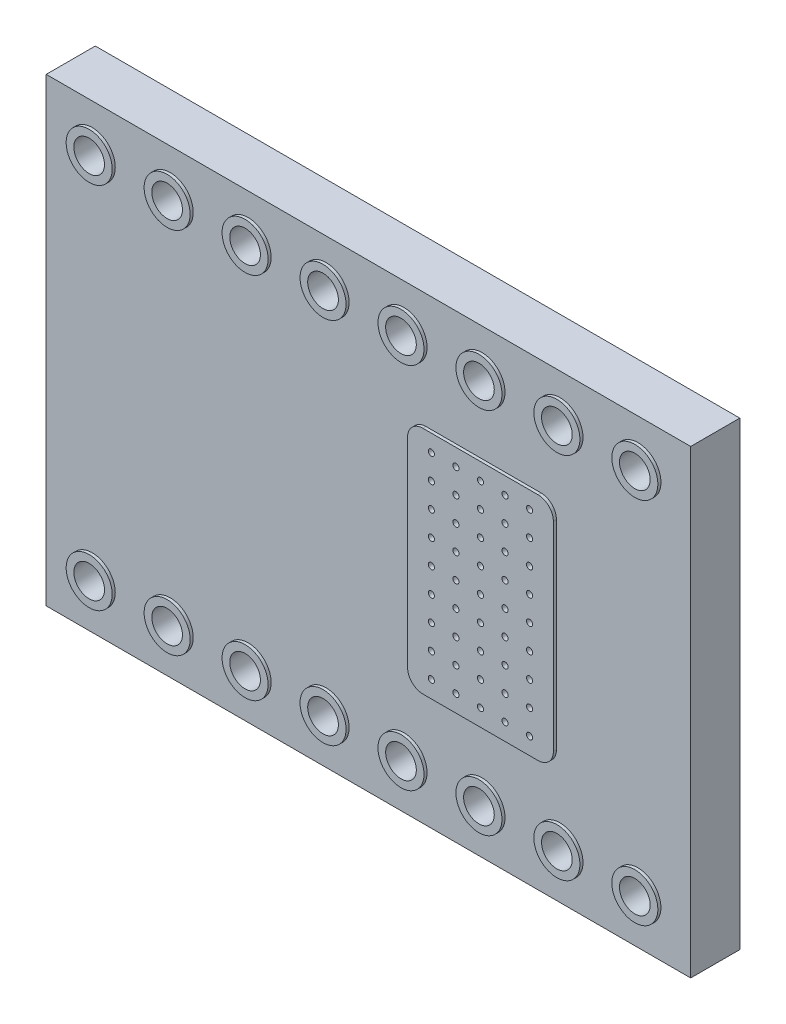
SolidWorks part; units mm, degrees
ref_plane "Front Plane" through (0, 0, 0) normal (0, 0, 1) x (1, 0, 0)
ref_plane "Top Plane" through (0, 0, 0) normal (0, 1, 0) x (1, 0, 0)
ref_plane "Right Plane" through (0, 0, 0) normal (1, 0, 0) x (0, 0, -1)
sketch "Sketch1" plane through (0, 0, 0) normal (0, 0, 1) x (1, 0, 0)
  line L1 (-10.5, 7.5) -> (10.5, 7.5)
  line L2 (-10.5, 7.5) -> (-10.5, -7.5)
  line L3 (-10.5, -7.5) -> (10.5, -7.5)
  line L4 (10.5, 7.5) -> (10.5, -7.5)
  line L5 (-10.5, 7.5) -> (10.5, -7.5) construction
  line L6 (-10.5, -7.5) -> (10.5, 7.5) construction
  point P0 (0, 0)
  dimension "D1" = 21
  dimension "D2" = 15
extrude "Boss-Extrude1" add sketch "Sketch1" along normal blind 1.6
sketch "Sketch2" plane through (0, 0, 1.6) normal (0, 0, 1) x (1, 0, 0)
  circle A0 centre (-9, 6) radius 0.75
  circle A1 centre (-9, -6) radius 0.75
  circle A2 centre (-6.46, 6) radius 0.75
  circle A3 centre (-6.46, -6) radius 0.75
  circle A4 centre (-3.92, 6) radius 0.75
  circle A5 centre (-3.92, -6) radius 0.75
  circle A6 centre (-1.38, 6) radius 0.75
  circle A7 centre (-1.38, -6) radius 0.75
  circle A8 centre (1.16, 6) radius 0.75
  circle A9 centre (1.16, -6) radius 0.75
  circle A10 centre (3.7, 6) radius 0.75
  circle A11 centre (3.7, -6) radius 0.75
  circle A12 centre (6.24, 6) radius 0.75
  circle A13 centre (6.24, -6) radius 0.75
  circle A14 centre (8.78, 6) radius 0.75
  circle A15 centre (8.78, -6) radius 0.75
  dimension "D3" = 1.5
  dimension "D4" = 1.5
  dimension "D1" = 12
  dimension "D2" = 6
  dimension "D6" = 9
  dimension "D5" = 8
extrude "Boss-Extrude2" add sketch "Sketch2" along normal blind 0.1 and the other way blind 1.7
sketch "Sketch3" plane through (0, 0, 1.7) normal (0, 0, 1) x (1, 0, 0)
  circle A0 centre (-9, 6) radius 0.5
  circle A1 centre (-9, -6) radius 0.5
  circle A2 centre (-6.46, 6) radius 0.5
  circle A3 centre (-6.46, -6) radius 0.5
  circle A4 centre (-3.92, 6) radius 0.5
  circle A5 centre (-3.92, -6) radius 0.5
  circle A6 centre (-1.38, 6) radius 0.5
  circle A7 centre (-1.38, -6) radius 0.5
  circle A8 centre (1.16, 6) radius 0.5
  circle A9 centre (1.16, -6) radius 0.5
  circle A10 centre (3.7, 6) radius 0.5
  circle A11 centre (3.7, -6) radius 0.5
  circle A12 centre (6.24, 6) radius 0.5
  circle A13 centre (6.24, -6) radius 0.5
  circle A14 centre (8.78, 6) radius 0.5
  circle A15 centre (8.78, -6) radius 0.5
  dimension "D1" = 1
  dimension "D2" = 1
  dimension "D3" = 8
extrude "Cut-Extrude1" cut sketch "Sketch3" against normal blind 2
sketch "Sketch4" plane through (0, 0, 0) normal (0, 0, -1) x (-1, 0, 0)
  line L1 (-5.625, 3.75) -> (-1.875, 3.75)
  line L2 (-6.125, 3.25) -> (-6.125, -3.25)
  line L3 (-5.625, -3.75) -> (-1.875, -3.75)
  line L4 (-1.375, 3.25) -> (-1.375, -3.25)
  line L5 (-6.125, 3.75) -> (-1.375, -3.75) construction
  line L6 (-6.125, -3.75) -> (-1.375, 3.75) construction
  arc A0 (-1.875, 3.75) -> (-1.375, 3.25) centre (-1.875, 3.25) cw
  arc A1 (-6.125, -3.25) -> (-5.625, -3.75) centre (-5.625, -3.25) ccw
  arc A2 (-5.625, 3.75) -> (-6.125, 3.25) centre (-5.625, 3.25) ccw
  arc A3 (-1.875, -3.75) -> (-1.375, -3.25) centre (-1.875, -3.25) ccw
  point P0 (-3.75, 0)
  dimension "D4" = 0.5
  dimension "D1" = 3.75
  dimension "D2" = 7.5
  dimension "D3" = 4.75
extrude "Boss-Extrude3" add sketch "Sketch4" along normal blind 0.1 and the other way blind 1.7
sketch "Sketch5" plane through (0, 0, -0.1) normal (0, 0, -1) x (-1, 0, 0)
  circle A0 centre (-3.75, 0) radius 0.1
  circle A1 centre (-2.95, 0) radius 0.1
  circle A2 centre (-2.15, 0) radius 0.1
  circle A3 centre (-3.75, 0) radius 0.1
  circle A4 centre (-2.95, 0) radius 0.1
  circle A5 centre (-4.55, 0) radius 0.1
  circle A6 centre (-3.75, 0) radius 0.1
  circle A7 centre (-4.55, 0) radius 0.1
  circle A8 centre (-5.35, 0) radius 0.1
  circle A9 centre (-3.75, -0.8) radius 0.1
  circle A10 centre (-4.55, -0.8) radius 0.1
  circle A11 centre (-5.35, -0.8) radius 0.1
  circle A12 centre (-2.95, -0.8) radius 0.1
  circle A13 centre (-2.15, -0.8) radius 0.1
  circle A14 centre (-3.75, -1.6) radius 0.1
  circle A15 centre (-4.55, -1.6) radius 0.1
  circle A16 centre (-5.35, -1.6) radius 0.1
  circle A17 centre (-2.95, -1.6) radius 0.1
  circle A18 centre (-2.15, -1.6) radius 0.1
  circle A19 centre (-3.75, -2.4) radius 0.1
  circle A20 centre (-4.55, -2.4) radius 0.1
  circle A21 centre (-5.35, -2.4) radius 0.1
  circle A22 centre (-2.95, -2.4) radius 0.1
  circle A23 centre (-2.15, -2.4) radius 0.1
  circle A24 centre (-3.75, -3.2) radius 0.1
  circle A25 centre (-4.55, -3.2) radius 0.1
  circle A26 centre (-5.35, -3.2) radius 0.1
  circle A27 centre (-2.95, -3.2) radius 0.1
  circle A28 centre (-2.15, -3.2) radius 0.1
  circle A29 centre (-3.75, 0) radius 0.1
  circle A30 centre (-4.55, 0) radius 0.1
  circle A31 centre (-5.35, 0) radius 0.1
  circle A32 centre (-2.95, 0) radius 0.1
  circle A33 centre (-2.15, 0) radius 0.1
  circle A34 centre (-3.75, -0.8) radius 0.1
  circle A35 centre (-4.55, -0.8) radius 0.1
  circle A36 centre (-5.35, -0.8) radius 0.1
  circle A37 centre (-2.95, -0.8) radius 0.1
  circle A38 centre (-2.15, -0.8) radius 0.1
  circle A39 centre (-3.75, -1.6) radius 0.1
  circle A40 centre (-4.55, -1.6) radius 0.1
  circle A41 centre (-5.35, -1.6) radius 0.1
  circle A42 centre (-2.95, -1.6) radius 0.1
  circle A43 centre (-2.15, -1.6) radius 0.1
  circle A44 centre (-3.75, -2.4) radius 0.1
  circle A45 centre (-4.55, -2.4) radius 0.1
  circle A46 centre (-5.35, -2.4) radius 0.1
  circle A47 centre (-2.95, -2.4) radius 0.1
  circle A48 centre (-2.15, -2.4) radius 0.1
  circle A49 centre (-3.75, 0.8) radius 0.1
  circle A50 centre (-4.55, 0.8) radius 0.1
  circle A51 centre (-5.35, 0.8) radius 0.1
  circle A52 centre (-2.95, 0.8) radius 0.1
  circle A53 centre (-2.15, 0.8) radius 0.1
  circle A54 centre (-3.75, 0) radius 0.1
  circle A55 centre (-4.55, 0) radius 0.1
  circle A56 centre (-5.35, 0) radius 0.1
  circle A57 centre (-2.95, 0) radius 0.1
  circle A58 centre (-2.15, 0) radius 0.1
  circle A59 centre (-3.75, -0.8) radius 0.1
  circle A60 centre (-4.55, -0.8) radius 0.1
  circle A61 centre (-5.35, -0.8) radius 0.1
  circle A62 centre (-2.95, -0.8) radius 0.1
  circle A63 centre (-2.15, -0.8) radius 0.1
  circle A64 centre (-3.75, -1.6) radius 0.1
  circle A65 centre (-4.55, -1.6) radius 0.1
  circle A66 centre (-5.35, -1.6) radius 0.1
  circle A67 centre (-2.95, -1.6) radius 0.1
  circle A68 centre (-2.15, -1.6) radius 0.1
  circle A69 centre (-3.75, 1.6) radius 0.1
  circle A70 centre (-4.55, 1.6) radius 0.1
  circle A71 centre (-5.35, 1.6) radius 0.1
  circle A72 centre (-2.95, 1.6) radius 0.1
  circle A73 centre (-2.15, 1.6) radius 0.1
  circle A74 centre (-3.75, 0.8) radius 0.1
  circle A75 centre (-4.55, 0.8) radius 0.1
  circle A76 centre (-5.35, 0.8) radius 0.1
  circle A77 centre (-2.95, 0.8) radius 0.1
  circle A78 centre (-2.15, 0.8) radius 0.1
  circle A79 centre (-3.75, 0) radius 0.1
  circle A80 centre (-4.55, 0) radius 0.1
  circle A81 centre (-5.35, 0) radius 0.1
  circle A82 centre (-2.95, 0) radius 0.1
  circle A83 centre (-2.15, 0) radius 0.1
  circle A84 centre (-3.75, -0.8) radius 0.1
  circle A85 centre (-4.55, -0.8) radius 0.1
  circle A86 centre (-5.35, -0.8) radius 0.1
  circle A87 centre (-2.95, -0.8) radius 0.1
  circle A88 centre (-2.15, -0.8) radius 0.1
  circle A89 centre (-3.75, 2.4) radius 0.1
  circle A90 centre (-4.55, 2.4) radius 0.1
  circle A91 centre (-5.35, 2.4) radius 0.1
  circle A92 centre (-2.95, 2.4) radius 0.1
  circle A93 centre (-2.15, 2.4) radius 0.1
  circle A94 centre (-3.75, 1.6) radius 0.1
  circle A95 centre (-4.55, 1.6) radius 0.1
  circle A96 centre (-5.35, 1.6) radius 0.1
  circle A97 centre (-2.95, 1.6) radius 0.1
  circle A98 centre (-2.15, 1.6) radius 0.1
  circle A99 centre (-3.75, 0.8) radius 0.1
  circle A100 centre (-4.55, 0.8) radius 0.1
  circle A101 centre (-5.35, 0.8) radius 0.1
  circle A102 centre (-2.95, 0.8) radius 0.1
  circle A103 centre (-2.15, 0.8) radius 0.1
  circle A104 centre (-3.75, 0) radius 0.1
  circle A105 centre (-4.55, 0) radius 0.1
  circle A106 centre (-5.35, 0) radius 0.1
  circle A107 centre (-2.95, 0) radius 0.1
  circle A108 centre (-2.15, 0) radius 0.1
  circle A109 centre (-3.75, 0.8) radius 0.1
  circle A110 centre (-4.55, 0.8) radius 0.1
  circle A111 centre (-5.35, 0.8) radius 0.1
  circle A112 centre (-2.95, 0.8) radius 0.1
  circle A113 centre (-2.15, 0.8) radius 0.1
  circle A114 centre (-3.75, 1.6) radius 0.1
  circle A115 centre (-4.55, 1.6) radius 0.1
  circle A116 centre (-5.35, 1.6) radius 0.1
  circle A117 centre (-2.95, 1.6) radius 0.1
  circle A118 centre (-2.15, 1.6) radius 0.1
  circle A119 centre (-3.75, 2.4) radius 0.1
  circle A120 centre (-4.55, 2.4) radius 0.1
  circle A121 centre (-5.35, 2.4) radius 0.1
  circle A122 centre (-2.95, 2.4) radius 0.1
  circle A123 centre (-2.15, 2.4) radius 0.1
  circle A124 centre (-3.75, 3.2) radius 0.1
  circle A125 centre (-4.55, 3.2) radius 0.1
  circle A126 centre (-5.35, 3.2) radius 0.1
  circle A127 centre (-2.95, 3.2) radius 0.1
  circle A128 centre (-2.15, 3.2) radius 0.1
  dimension "D2" = 0.2
  dimension "D1" = 3.75
  dimension "D3" = 3
  dimension "D4" = 3
  dimension "D5" = 5
  dimension "D6" = 5
extrude "Cut-Extrude2" cut sketch "Sketch5" against normal blind 1.8
